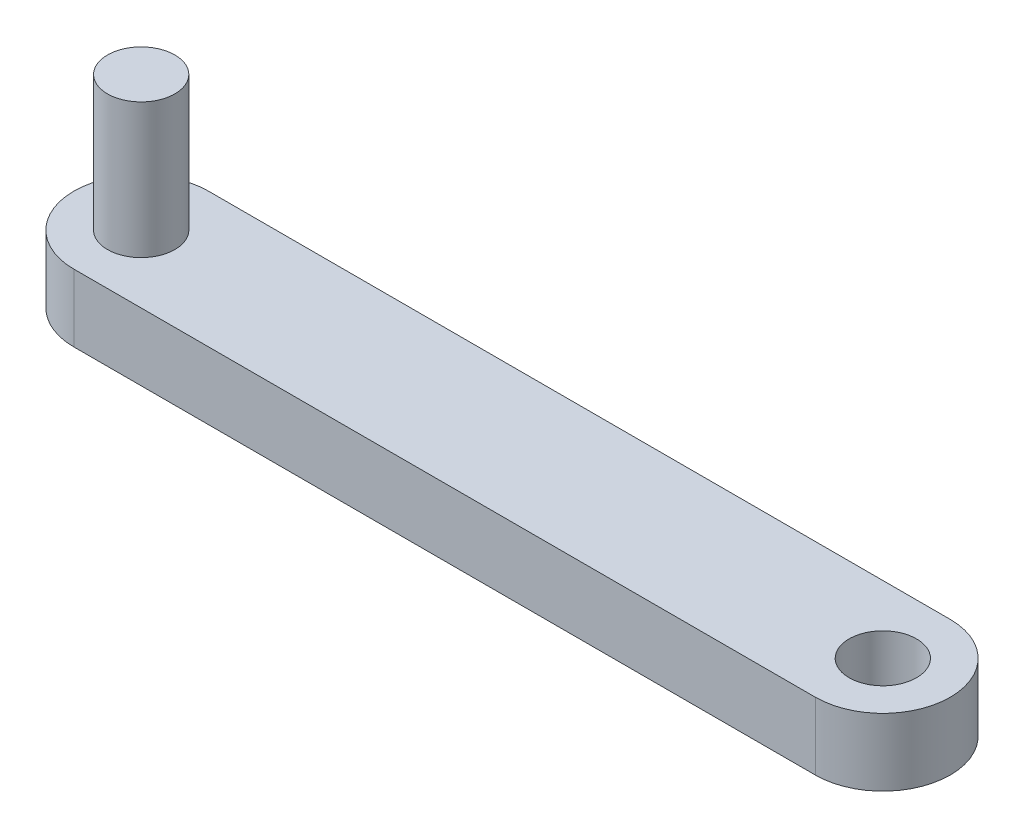
SolidWorks part; units mm, degrees
ref_plane "Front Plane" through (0, 0, 0) normal (0, 0, 1) x (1, 0, 0)
ref_plane "Top Plane" through (0, 0, 0) normal (0, 1, 0) x (1, 0, 0)
ref_plane "Right Plane" through (0, 0, 0) normal (1, 0, 0) x (0, 0, -1)
sketch "Sketch1" plane through (0, 0, 0) normal (0, 1, 0) x (1, 0, 0)
  line L1 (-55, -10) -> (55, -10)
  line L3 (-55, 10) -> (55, 10)
  line L5 (-55, -10) -> (55, 10) construction
  line L6 (-55, 10) -> (55, -10) construction
  arc A0 (-55, 10) -> (-55, -10) centre (-55, 0) ccw
  arc A1 (55, 10) -> (55, -10) centre (55, 0) cw
  circle A2 centre (-55, 0) radius 5
  circle A3 centre (55, 0) radius 5
  point P0 (0, 0)
  dimension "D3" = 10
  dimension "D4" = 10
  dimension "D1" = 20
  dimension "D2" = 110
extrude "Boss-Extrude1" add sketch "Sketch1" along normal mid plane 10
sketch "Sketch2" plane through (0, 0, 0) normal (0, 1, 0) x (1, 0, 0)
  circle A0 centre (-55, 0) radius 5
  dimension "D1" = 10
extrude "Boss-Extrude2" add sketch "Sketch2" along normal blind 25 and the other way blind 5
